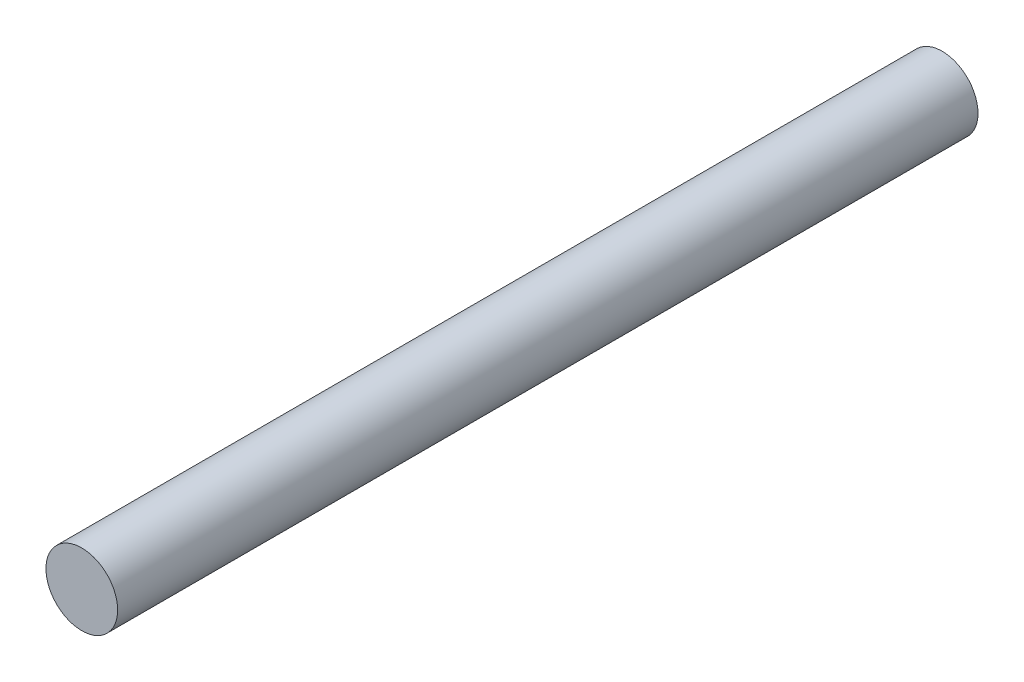
SolidWorks part; units mm, degrees
ref_plane "Alzado" through (0, 0, 0) normal (0, 0, 1) x (1, 0, 0)
ref_plane "Planta" through (0, 0, 0) normal (0, 1, 0) x (1, 0, 0)
ref_plane "Vista lateral" through (0, 0, 0) normal (1, 0, 0) x (0, 0, -1)
sketch "Croquis1" plane through (0, 0, 0) normal (0, 0, 1) x (1, 0, 0)
  circle A0 centre (0, 0) radius 2.5
  dimension "D1" = 5
extrude "Saliente-Extruir1" add sketch "Croquis1" along normal blind 60
